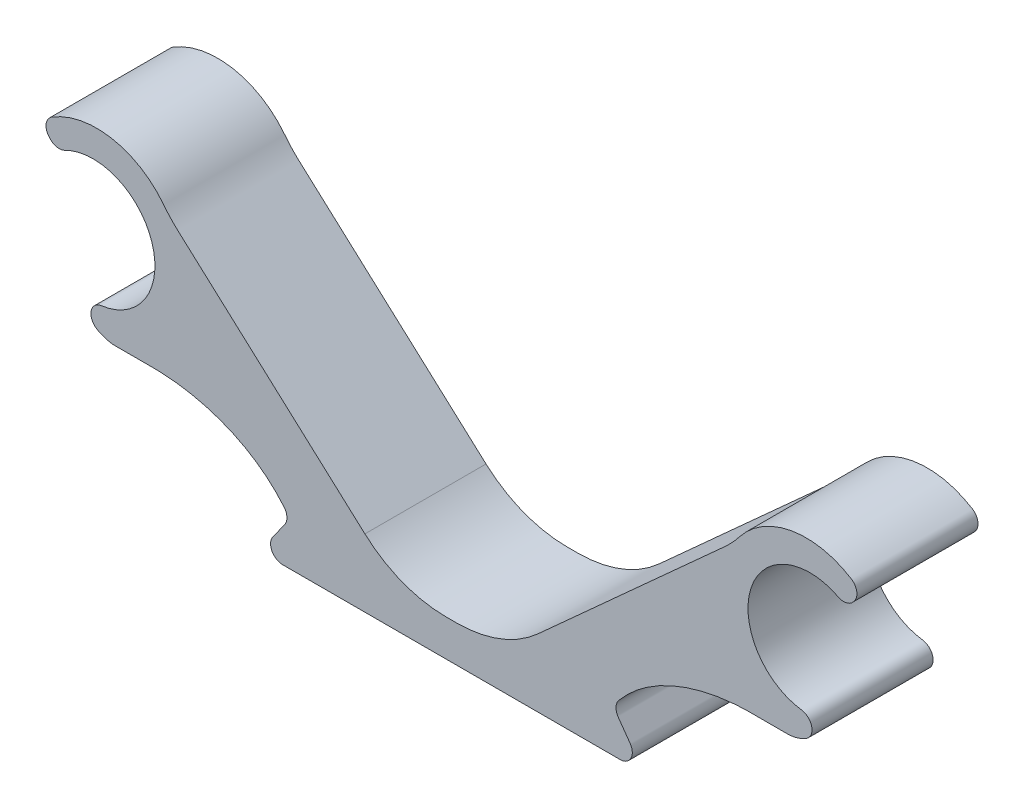
SolidWorks part; units mm, degrees
material "PF"
ref_plane "Front Plane" through (0, 0, 0) normal (0, 0, 1) x (1, 0, 0)
ref_plane "Top Plane" through (0, 0, 0) normal (0, 1, 0) x (1, 0, 0)
ref_plane "Right Plane" through (0, 0, 0) normal (1, 0, 0) x (0, 0, -1)
sketch "Sketch1" plane through (0, 0, 0) normal (0, 0, 1) x (1, 0, 0)
  line L0 (-18.1667, 17.5) -> (53.1667, 17.5) construction
  line L2 (-14.7494, 1.5791) -> (-13.7695, 2.9586)
  line L3 (-22.5726, 19.5522) -> (-7.1459, 5.6011)
  line L4 (0.4384, 3.0179) -> (-0.4384, 3.0179)
  line L5 (13.9342, 0) -> (-13.9342, 0)
  line L6 (-33.2242, 20.9572) -> (-33.1379, 20.8606)
  line L7 (-27.7843, 8.7419) -> (-25.3187, 8.7419)
  line L8 (27.7843, 8.7419) -> (25.3187, 8.7419)
  line L9 (33.2242, 20.9572) -> (33.1379, 20.8606)
  line L10 (22.5726, 19.5522) -> (7.1459, 5.6011)
  line L11 (14.7494, 1.5791) -> (13.7695, 2.9586)
  arc A0 (-31.9337, 20.6377) -> (-28.9066, 11.0365) centre (-29.5931, 16.0979) cw
  arc A1 (-7.1459, 5.6011) -> (-0.4384, 3.0179) centre (-0.4384, 13.0179) ccw
  arc A2 (-33.0103, 22.4698) -> (-23.7645, 20.8371) centre (-29.2888, 16.5487) cw
  arc A3 (-14.7494, 1.5791) -> (-13.9342, 0) centre (-13.9342, 1) ccw
  arc A4 (-22.5726, 19.5522) -> (-23.7645, 20.8371) centre (-15.8652, 26.9691) cw
  arc A5 (-13.7695, 2.9586) -> (-13.8144, 4.1754) centre (-14.5847, 3.5377) ccw
  arc A6 (-28.9066, 11.0365) -> (-29.3232, 9.2112) centre (-28.7721, 10.0456) ccw
  arc A7 (-33.2242, 20.9572) -> (-33.0103, 22.4698) centre (-32.4782, 21.6231) cw
  arc A8 (-33.1379, 20.8606) -> (-31.9337, 20.6377) centre (-32.3919, 21.5265) ccw
  arc A9 (33.1379, 20.8606) -> (31.9337, 20.6377) centre (32.3919, 21.5265) cw
  arc A10 (33.2242, 20.9572) -> (33.0103, 22.4698) centre (32.4782, 21.6231) ccw
  arc A11 (28.9066, 11.0365) -> (29.3232, 9.2112) centre (28.7721, 10.0456) cw
  arc A12 (13.7695, 2.9586) -> (13.8144, 4.1754) centre (14.5847, 3.5377) cw
  arc A13 (22.5726, 19.5522) -> (23.7645, 20.8371) centre (15.8652, 26.9691) ccw
  arc A14 (14.7494, 1.5791) -> (13.9342, 0) centre (13.9342, 1) cw
  arc A15 (33.0103, 22.4698) -> (23.7645, 20.8371) centre (29.2888, 16.5487) ccw
  arc A16 (7.1459, 5.6011) -> (0.4384, 3.0179) centre (0.4384, 13.0179) cw
  arc A17 (31.9337, 20.6377) -> (28.9066, 11.0365) centre (29.5931, 16.0979) ccw
  spline S0 degree 3 poles (-13.8144, 4.1754) (-14.4175, 4.9039) (-17.5678, 7.7912) (-22.0616, 8.8419) (-25.3187, 8.7419) knots 0.056599 0.056599 0.056599 0.056599 0.264505 1 1 1 1
  spline S1 degree 3 poles (-29.3232, 9.2112) (-28.9117, 8.9394) (-28.2724, 8.7434) (-27.7843, 8.7419) knots 0.586597 0.586597 0.586597 0.586597 1 1 1 1
  spline S2 degree 3 poles (29.3232, 9.2112) (28.9117, 8.9394) (28.2724, 8.7434) (27.7843, 8.7419) knots 0.586597 0.586597 0.586597 0.586597 1 1 1 1
  spline S3 degree 3 poles (13.8144, 4.1754) (14.4175, 4.9039) (17.5678, 7.7912) (22.0616, 8.8419) (25.3187, 8.7419) knots 0.056599 0.056599 0.056599 0.056599 0.264505 1 1 1 1
  dimension "D1" = 10
  dimension "D2" = 1
  dimension "D3" = 10
  dimension "D4" = 1
  dimension "D5" = 1
  dimension "D6" = 1
ref_plane "Plane1" through (0, 0, 10) normal (0, 0, 1) x (1, 0, 0)
sketch "Sketch7" plane through (0, 0, 10) normal (0, 0, 1) x (1, 0, 0)
  line L0 (-18.1667, 17.5) -> (53.1667, 17.5) construction
  line L2 (-14.7494, 1.5791) -> (-13.7695, 2.9586)
  line L3 (-22.5726, 19.5522) -> (-7.1459, 5.6011)
  line L4 (0.4384, 3.0179) -> (-0.4384, 3.0179)
  line L5 (13.9342, 0) -> (-13.9342, 0)
  line L6 (-33.2242, 20.9572) -> (-33.1379, 20.8606)
  line L7 (-27.7843, 8.7419) -> (-25.3187, 8.7419)
  line L8 (27.7843, 8.7419) -> (25.3187, 8.7419)
  line L9 (33.2242, 20.9572) -> (33.1379, 20.8606)
  line L10 (22.5726, 19.5522) -> (7.1459, 5.6011)
  line L11 (14.7494, 1.5791) -> (13.7695, 2.9586)
  arc A0 (-31.9337, 20.6377) -> (-28.9066, 11.0365) centre (-29.5931, 16.0979) cw
  arc A1 (-7.1459, 5.6011) -> (-0.4384, 3.0179) centre (-0.4384, 13.0179) ccw
  arc A2 (-33.0103, 22.4698) -> (-23.7645, 20.8371) centre (-29.2888, 16.5487) cw
  arc A3 (-14.7494, 1.5791) -> (-13.9342, 0) centre (-13.9342, 1) ccw
  arc A4 (-22.5726, 19.5522) -> (-23.7645, 20.8371) centre (-15.8652, 26.9691) cw
  arc A5 (-13.7695, 2.9586) -> (-13.8144, 4.1754) centre (-14.5847, 3.5377) ccw
  arc A6 (-28.9066, 11.0365) -> (-29.3232, 9.2112) centre (-28.7721, 10.0456) ccw
  arc A7 (-33.2242, 20.9572) -> (-33.0103, 22.4698) centre (-32.4782, 21.6231) cw
  arc A8 (-33.1379, 20.8606) -> (-31.9337, 20.6377) centre (-32.3919, 21.5265) ccw
  arc A9 (33.1379, 20.8606) -> (31.9337, 20.6377) centre (32.3919, 21.5265) cw
  arc A10 (33.2242, 20.9572) -> (33.0103, 22.4698) centre (32.4782, 21.6231) ccw
  arc A11 (28.9066, 11.0365) -> (29.3232, 9.2112) centre (28.7721, 10.0456) cw
  arc A12 (13.7695, 2.9586) -> (13.8144, 4.1754) centre (14.5847, 3.5377) cw
  arc A13 (22.5726, 19.5522) -> (23.7645, 20.8371) centre (15.8652, 26.9691) ccw
  arc A14 (14.7494, 1.5791) -> (13.9342, 0) centre (13.9342, 1) cw
  arc A15 (33.0103, 22.4698) -> (23.7645, 20.8371) centre (29.2888, 16.5487) ccw
  arc A16 (7.1459, 5.6011) -> (0.4384, 3.0179) centre (0.4384, 13.0179) cw
  arc A17 (31.9337, 20.6377) -> (28.9066, 11.0365) centre (29.5931, 16.0979) ccw
  spline S0 degree 3 poles (-13.8144, 4.1754) (-14.4175, 4.9039) (-17.5678, 7.7912) (-22.0616, 8.8419) (-25.3187, 8.7419) knots 0.056599 0.056599 0.056599 0.056599 0.264505 1 1 1 1
  spline S1 degree 3 poles (-29.3232, 9.2112) (-28.9117, 8.9394) (-28.2724, 8.7434) (-27.7843, 8.7419) knots 0.586597 0.586597 0.586597 0.586597 1 1 1 1
  spline S2 degree 3 poles (29.3232, 9.2112) (28.9117, 8.9394) (28.2724, 8.7434) (27.7843, 8.7419) knots 0.586597 0.586597 0.586597 0.586597 1 1 1 1
  spline S3 degree 3 poles (13.8144, 4.1754) (14.4175, 4.9039) (17.5678, 7.7912) (22.0616, 8.8419) (25.3187, 8.7419) knots 0.056599 0.056599 0.056599 0.056599 0.264505 1 1 1 1
  dimension "D1" = 10
  dimension "D2" = 1
  dimension "D3" = 10
  dimension "D4" = 1
  dimension "D5" = 1
  dimension "D6" = 1
loft "Loft2" add profiles "Sketch1", "Sketch7"
